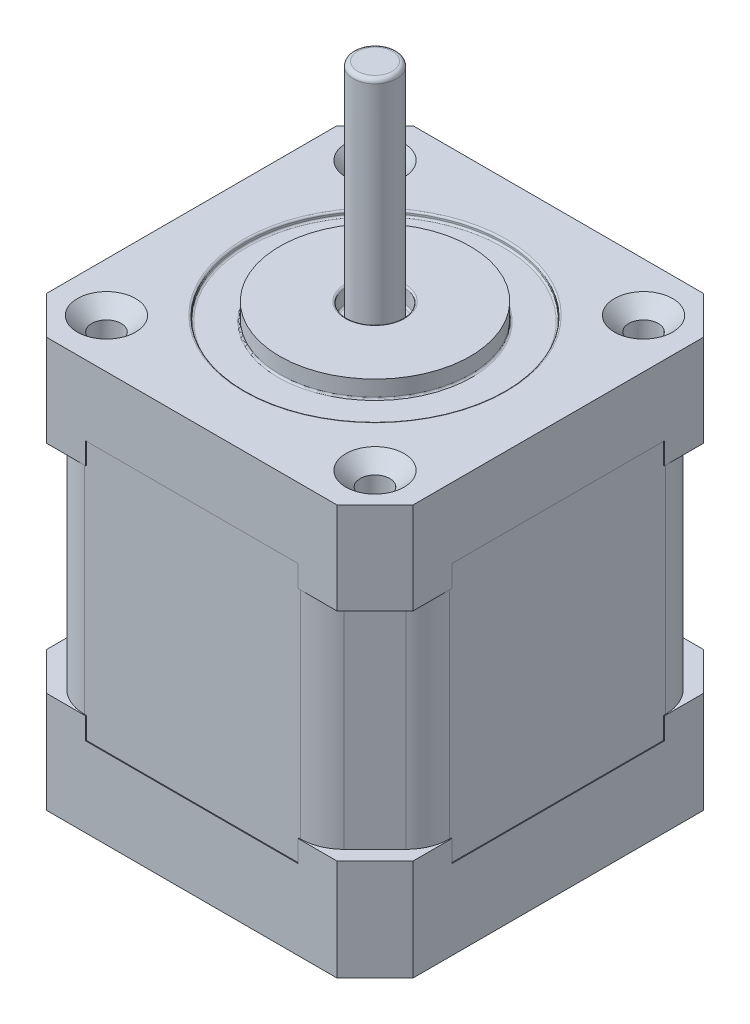
SolidWorks part; units mm, degrees
ref_plane "Alzado" through (0, 0, 0) normal (0, 0, 1) x (1, 0, 0)
ref_plane "Planta" through (0, 0, 0) normal (0, 1, 0) x (1, 0, 0)
ref_plane "Vista lateral" through (0, 0, 0) normal (1, 0, 0) x (0, 0, -1)
sketch "Croquis1" plane through (0, 0, 0) normal (0, 1, 0) x (1, 0, 0)
  line L0 (-16.75, 21.15) -> (16.75, 21.15)
  line L1 (16.75, 21.15) -> (21.15, 16.75)
  line L2 (21.15, 16.75) -> (21.15, -16.75)
  line L3 (21.15, -16.75) -> (16.75, -21.15)
  line L4 (16.75, -21.15) -> (-16.75, -21.15)
  line L5 (-16.75, -21.15) -> (-21.15, -16.75)
  line L6 (-21.15, -16.75) -> (-21.15, 16.75)
  line L7 (-21.15, 16.75) -> (-16.75, 21.15)
  line L8 (-18.95, -18.95) -> (18.95, 18.95) construction
  line L10 (-39.2916, 0) -> (35.7633, 0) construction
  line L11 (0, 36.7954) -> (0, -37.5687) construction
  line L12 (0, -55) -> (0, 55) construction
  dimension "D1" = 42.3
  dimension "D2" = 4.4
extrude "Saliente-Extruir1" add sketch "Croquis1" along normal blind 9.2
sketch "Croquis2" plane through (0, 9.2, 0) normal (0, 1, 0) x (1, 0, 0)
  line L0 (-12.25, 12.25) -> (-12.25, 21.15)
  line L1 (12.25, 21.15) -> (16.75, 21.15)
  line L2 (16.75, 21.15) -> (-16.75, 21.15) construction
  line L3 (16.75, 21.15) -> (21.15, 16.75)
  line L4 (21.15, 16.75) -> (21.15, 12.25)
  line L5 (21.15, -16.75) -> (21.15, 16.75) construction
  line L6 (21.15, 12.25) -> (12.25, 12.25)
  line L7 (-21.15, 12.25) -> (-12.25, 12.25)
  line L8 (12.25, 12.25) -> (12.25, 21.15)
  line L9 (0, 44.4821) -> (0, -50.5271) construction
  line L10 (49.3666, 0) -> (-35.8489, 0) construction
  line L11 (-5.06, 0) -> (5.06, 0) construction
  line L12 (-21.15, 16.75) -> (-21.15, 12.25)
  line L13 (-16.75, 21.15) -> (-21.15, 16.75)
  line L14 (-12.25, 21.15) -> (-16.75, 21.15)
  line L15 (12.25, -12.25) -> (12.25, -21.15)
  line L16 (21.15, -12.25) -> (12.25, -12.25)
  line L17 (21.15, -16.75) -> (21.15, -12.25)
  line L18 (16.75, -21.15) -> (21.15, -16.75)
  line L19 (12.25, -21.15) -> (16.75, -21.15)
  line L20 (-12.25, -21.15) -> (-16.75, -21.15)
  line L21 (-16.75, -21.15) -> (-21.15, -16.75)
  line L22 (-21.15, -16.75) -> (-21.15, -12.25)
  line L23 (-21.15, -12.25) -> (-12.25, -12.25)
  line L24 (-12.25, -12.25) -> (-12.25, -21.15)
  dimension "D1" = 4.5
extrude "Saliente-Extruir2" add sketch "Croquis2" along normal blind 2.5
hole_wizard "Refrentado para tornillo con cabeza troncocónica de M31" positions "Croquis4" profile "Croquis3" counterbore size "M3" standard "Métrico Ansi" end condition through all
sketch "Croquis4" plane through (0, 0, 0) normal (0, -1, 0) x (1, 0, 0)
  line L4 (29.49, 0) -> (-30.8346, 0) construction
  line L6 (0, 26.3919) -> (0, -28.4859) construction
  point P0 (15.5, 15.5)
  point P42 (15.5, -15.5)
  point P49 (-15.5, 15.5)
  point P50 (-15.5, -15.5)
  dimension "D1" = 31
  dimension "D2" = 31
sketch "Croquis3" plane through (15.5, 0, 15.5) normal (1, 0, 0) x (0, 0, -1)
  line L0 (0, 0) -> (0, 11.7)
  line L1 (0, 11.7) -> (1.7, 11.7)
  line L3 (1.7, 11.7) -> (1.7, 2.4)
  line L4 (1.7, 2.4) -> (3.5, 2.4)
  line L5 (3.5, 2.4) -> (3.5, 0)
  line L7 (3.5, 0) -> (0, 0)
  line L11 (0, -6.35) -> (0, 107.95) construction
  dimension "Diámetro de taladro hasta el siguiente" = 3.4
  dimension "Profundidad de taladro hasta el siguiente" = 11.7
  dimension "Diámetro de refrentado" = 7
  dimension "Profundidad de refrentado" = 2.4
sketch "Croquis5" plane through (0, 9.2, 0) normal (0, 1, 0) x (1, 0, 0)
  line L0 (-14.5307, 21.05) -> (14.5307, 21.05)
  line L2 (14.5307, 21.05) -> (21.05, 14.5307)
  line L3 (21.05, 14.5307) -> (21.05, -14.5307)
  line L4 (21.15, -12.25) -> (21.15, 12.25) construction
  line L5 (21.05, -14.5307) -> (14.5307, -21.05)
  line L7 (14.5307, -21.05) -> (-14.5307, -21.05)
  line L8 (-14.5307, -21.05) -> (-21.05, -14.5307)
  line L9 (-21.15, 12.25) -> (-21.15, -12.25) construction
  line L10 (-21.05, -14.5307) -> (-21.05, 14.5307)
  line L11 (-21.05, 14.5307) -> (-14.5307, 21.05)
  line L12 (21.15, 16.75) -> (16.75, 21.15) construction
  line L14 (-12.25, -21.15) -> (12.25, -21.15) construction
  line L15 (12.25, 21.15) -> (-12.25, 21.15) construction
  point P18 (18.95, 18.95)
  dimension "D1" = 1.64
  dimension "D2" = 0.1
  dimension "D3" = 0.1
  dimension "D4" = 0.1
extrude "Saliente-Extruir3" add sketch "Croquis5" along normal blind 30
fillet "Redondeo1" radius 5 8 edges at (-21.05, 25.45, 14.5307) (-21.05, 25.45, -14.5307) (-14.5307, 25.45, -21.05) (14.5307, 25.45, -21.05) (21.05, 25.45, -14.5307) (21.05, 25.45, 14.5307) (14.5307, 25.45, 21.05) (-14.5307, 25.45, 21.05)
sketch "Croquis7" plane through (0, 39.2, 0) normal (0, 1, 0) x (1, 0, 0)
  line L0 (-16.75, 21.15) -> (16.75, 21.15)
  line L1 (16.75, 21.15) -> (21.15, 16.75)
  line L2 (21.15, 16.75) -> (21.15, -16.75)
  line L3 (21.15, -16.75) -> (16.75, -21.15)
  line L4 (16.75, -21.15) -> (-16.75, -21.15)
  line L5 (-16.75, -21.15) -> (-21.15, -16.75)
  line L6 (-21.15, -16.75) -> (-21.15, 16.75)
  line L7 (-21.15, 16.75) -> (-16.75, 21.15)
  line L8 (-18.95, -18.95) -> (18.95, 18.95) construction
  line L9 (-49.9602, 0) -> (25.0947, 0) construction
  line L10 (0, 47.065) -> (0, -27.2991) construction
  line L11 (-16.75, -21.15) -> (16.75, -21.15) construction
  line L12 (21.15, -16.75) -> (21.15, 16.75) construction
  dimension "D1" = 42.3
  dimension "D2" = 4.4
extrude "Saliente-Extruir4" add sketch "Croquis7" along normal blind 8.1
sketch "Croquis9" plane through (0, 39.2, 0) normal (0, -1, 0) x (1, 0, 0)
  line L1 (16.75, 21.15) -> (21.15, 16.75) construction
  line B0 (-12.25, 12.25) -> (-12.25, 21.15)
  line B1 (12.25, 21.15) -> (16.75, 21.15)
  line B2 (16.75, 21.15) -> (21.15, 16.75)
  line B3 (21.15, 16.75) -> (21.15, 12.25)
  line B4 (21.15, 12.25) -> (12.25, 12.25)
  line B5 (-21.15, 12.25) -> (-12.25, 12.25)
  line B6 (12.25, 12.25) -> (12.25, 21.15)
  line B7 (-21.15, 16.75) -> (-21.15, 12.25)
  line B8 (-16.75, 21.15) -> (-21.15, 16.75)
  line B9 (-12.25, 21.15) -> (-16.75, 21.15)
  line B10 (12.25, -12.25) -> (12.25, -21.15)
  line B11 (21.15, -12.25) -> (12.25, -12.25)
  line B12 (21.15, -16.75) -> (21.15, -12.25)
  line B13 (16.75, -21.15) -> (21.15, -16.75)
  line B14 (12.25, -21.15) -> (16.75, -21.15)
  line B15 (-12.25, -21.15) -> (-16.75, -21.15)
  line B16 (-16.75, -21.15) -> (-21.15, -16.75)
  line B17 (-21.15, -16.75) -> (-21.15, -12.25)
  line B18 (-21.15, -12.25) -> (-12.25, -12.25)
  line B19 (-12.25, -12.25) -> (-12.25, -21.15)
  dimension "D1" = 0
  dimension "D2" = 0
sketch_block_instance "Bloque1-1"
sketch_block "Bloque1" parameters "D1"=4.5
extrude "Saliente-Extruir5" add sketch "Croquis9" along normal blind 2.5
hole_wizard "Refrentado para tornillo tapón con cabeza plana de clavija de M31" positions "Croquis3D1" profile "Croquis13" countersink size "M3" standard "Métrico Ansi"
sketch3d "Croquis3D1"
  circle A0 centre (15.5, 2.4, -15.5) radius 1.7 construction
  circle A1 centre (-15.5, 2.4, -15.5) radius 1.7 construction
  circle A2 centre (-15.5, 2.4, 15.5) radius 1.7 construction
  circle A3 centre (15.5, 2.4, 15.5) radius 1.7 construction
  point P0 (-15.5, 47.3, -15.5)
  point P2 (15.5, 47.3, -15.5)
  point P4 (15.5, 47.3, 15.5)
  point P6 (-15.5, 47.3, 15.5)
  point P14 (15.5, 0.7, -15.5)
  point P18 (-15.5, 0.7, -15.5)
  point P22 (-15.5, 0.7, 15.5)
  point P26 (15.5, 0.7, 15.5)
sketch "Croquis13" plane through (-15.5, 47.3, -15.5) normal (1, 0, 0) x (0, 0, 1)
  line L0 (0, 0) -> (0, 11.6215)
  line L1 (0, 11.6215) -> (1.7, 10.6)
  line L2 (1.7, 10.6) -> (1.7, 1.66)
  line L3 (1.7, 1.66) -> (3.36, 0)
  line L5 (3.36, 0) -> (0, 0)
  line L6 (-1.7, 1.66) -> (-3.36, 0) construction
  line L10 (0, 11.6215) -> (-1.7, 10.6) construction
  line L11 (0, -6.35) -> (0, 107.95) construction
  dimension "Diámetro de taladro" = 3.4
  dimension "Profundidad de taladro" = 10.6
  dimension "Ángulo de avellanado cercano" = 6.72
  dimension "Ángulo de avellanado lejano" = 90
  dimension "Ángulo de perforador" = 118
sketch "Croquis14" plane through (0, 47.3, 0) normal (0, 1, 0) x (1, 0, 0)
  circle A0 centre (0, 0) radius 15
extrude "Cortar-Extruir1" cut sketch "Croquis14" against normal blind 0.6
sketch "Croquis15" plane through (0, 46.7, 0) normal (0, 1, 0) x (1, 0, 0)
  circle A0 centre (0, 0) radius 11
  circle A1 centre (0, 0) radius 3.25
  dimension "D1" = 6.5
  dimension "D2" = 22
extrude "Saliente-Extruir6" add sketch "Croquis15" along normal blind 2
fillet "Redondeo2" radius 0.2 5 edges at (0, 46.7, 11) (0, 46.7, 15) (0, 47.3, 15) (0, 46.7, 3.25) (0, 48.7, 3.25)
sketch "Croquis16" plane through (0, 46.7, 0) normal (0, 1, 0) x (1, 0, 0)
  circle A0 centre (0, 0) radius 2.5
  dimension "D1" = 5
extrude "Saliente-Extruir7" add sketch "Croquis16" along normal blind 26
fillet "Redondeo3" radius 0.5 1 edges at (0, 72.7, 2.5)
